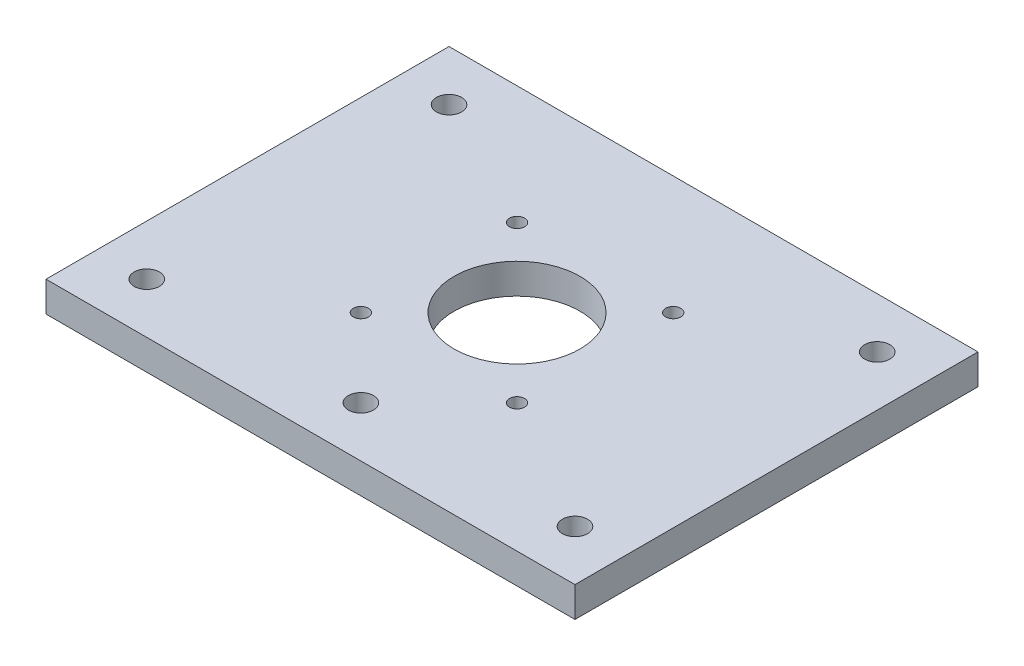
SolidWorks part; units mm, degrees
material "Acrylic (Medium-high impact)"
ref_plane "Front Plane" through (0, 0, 0) normal (0, 0, 1) x (1, 0, 0)
ref_plane "Top Plane" through (0, 0, 0) normal (0, 1, 0) x (1, 0, 0)
ref_plane "Right Plane" through (0, 0, 0) normal (1, 0, 0) x (0, 0, -1)
sketch "Sketch1" plane through (0, 0, 0) normal (0, 1, 0) x (1, 0, 0)
  line L0 (0, 0) -> (-52.5, 0)
  line L1 (-52.5, 0) -> (-52.5, 80)
  line L2 (-52.5, 80) -> (52.5, 80)
  line L3 (52.5, 80) -> (52.5, 0)
  line L4 (52.5, 0) -> (0, 0)
  dimension "D1" = 105
  dimension "D2" = 80
extrude "Boss-Extrude1" add sketch "Sketch1" along normal blind 6
sketch "Sketch2" plane through (0, 6, 0) normal (0, 1, 0) x (1, 0, 0)
  line L0 (-42.5, 70) -> (-42.5, 10) construction
  line L1 (-42.5, 10) -> (42.5, 10) construction
  line L2 (42.5, 10) -> (42.5, 70) construction
  line L3 (42.5, 70) -> (-42.5, 70) construction
  line L4 (-52.5, 80) -> (-52.5, 0) construction
  line L5 (52.5, 0) -> (52.5, 80) construction
  line L6 (-52.5, 0) -> (52.5, 0) construction
  line L7 (52.5, 80) -> (-52.5, 80) construction
  line L8 (0, 0) -> (0, 41) construction
  line L10 (15.5, 25.5) -> (-15.5, 25.5) construction
  line L11 (15.5, 25.5) -> (15.5, 56.5) construction
  line L12 (15.5, 56.5) -> (-15.5, 56.5) construction
  line L13 (-15.5, 25.5) -> (-15.5, 56.5) construction
  line L14 (15.5, 25.5) -> (-15.5, 56.5) construction
  line L15 (15.5, 56.5) -> (-15.5, 25.5) construction
  circle A0 centre (-42.5, 70) radius 2.5
  circle A1 centre (42.5, 70) radius 2.5
  circle A2 centre (42.5, 10) radius 2.5
  circle A3 centre (0, 10) radius 2.5
  circle A4 centre (-42.5, 10) radius 2.5
  circle A5 centre (0, 41) radius 12.5
  circle A6 centre (-15.5, 56.5) radius 1.5
  circle A7 centre (15.5, 56.5) radius 1.5
  circle A8 centre (-15.5, 25.5) radius 1.5
  circle A9 centre (15.5, 25.5) radius 1.5
  dimension "D1" = 5
  dimension "D6" = 25
  dimension "D8" = 3
  dimension "D2" = 10
  dimension "D3" = 10
  dimension "D4" = 10
  dimension "D5" = 10
  dimension "D7" = 41
  dimension "D9" = 31
extrude "Cut-Extrude1" cut sketch "Sketch2" against normal through all
